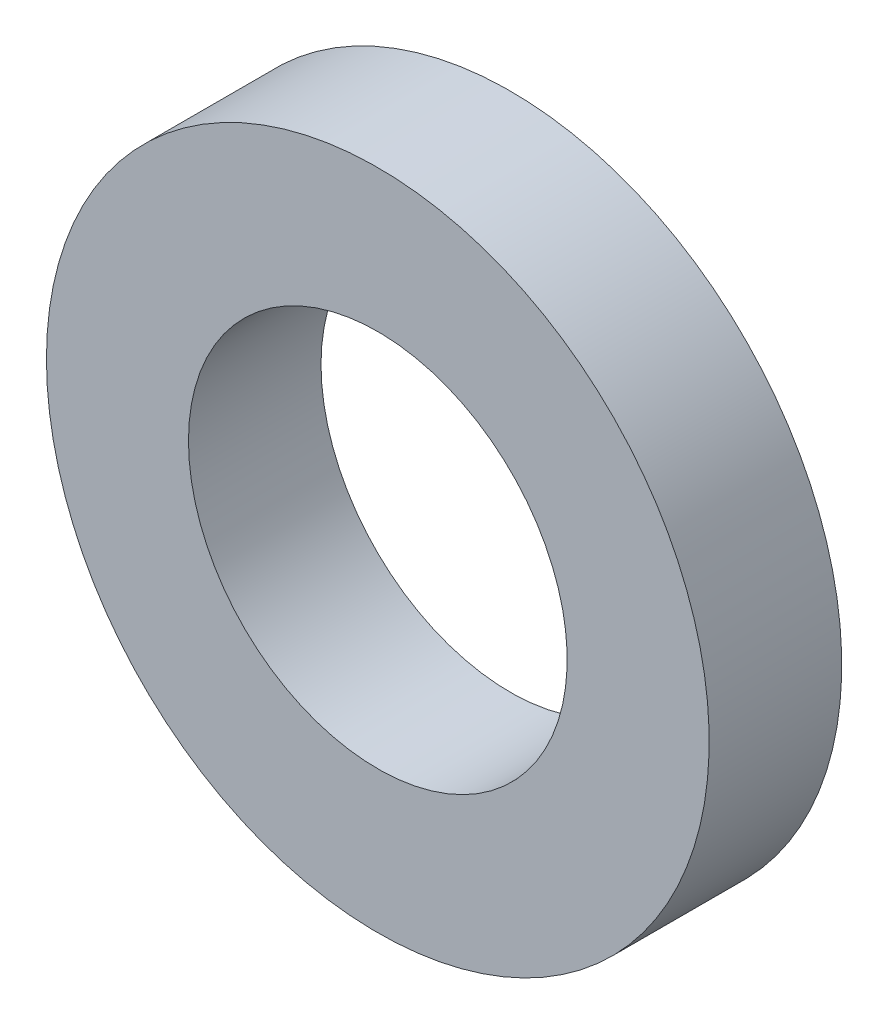
SolidWorks part; units mm, degrees
ref_plane "前视基准面" through (0, 0, 0) normal (0, 0, 1) x (1, 0, 0)
ref_plane "上视基准面" through (0, 0, 0) normal (0, 1, 0) x (1, 0, 0)
ref_plane "右视基准面" through (0, 0, 0) normal (1, 0, 0) x (0, 0, -1)
sketch "草图1" plane through (0, 0, 0) normal (0, 0, 1) x (1, 0, 0)
  circle A0 centre (0, 0) radius 20
  circle A1 centre (0, 0) radius 35
  dimension "D1" = 40
  dimension "D2" = 70
extrude "凸台-拉伸1" add sketch "草图1" along normal blind 14
